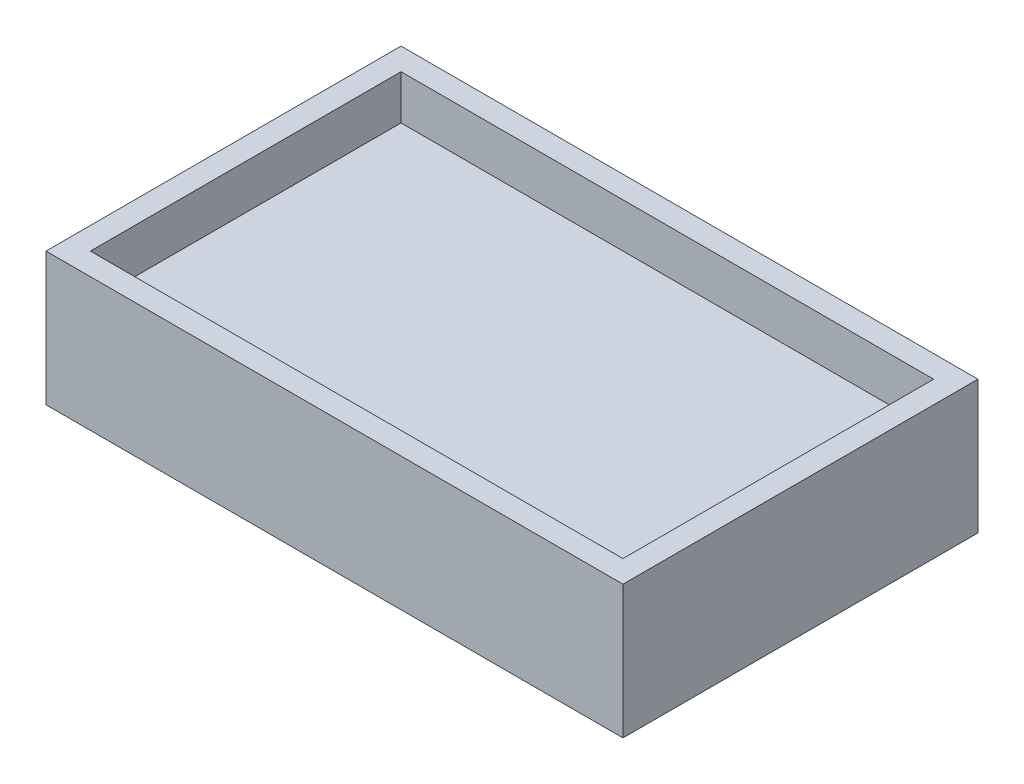
SolidWorks part; units mm, degrees
ref_plane "Front Plane" through (0, 0, 0) normal (0, 0, 1) x (1, 0, 0)
ref_plane "Top Plane" through (0, 0, 0) normal (0, 1, 0) x (1, 0, 0)
ref_plane "Right Plane" through (0, 0, 0) normal (1, 0, 0) x (0, 0, -1)
sketch "Sketch2" plane through (0, 0, 0) normal (0, 1, 0) x (1, 0, 0)
  line L1 (-65, 40) -> (65, 40)
  line L2 (-65, 40) -> (-65, -40)
  line L3 (-65, -40) -> (65, -40)
  line L4 (65, 40) -> (65, -40)
  line L5 (-65, 40) -> (65, -40) construction
  line L6 (-65, -40) -> (65, 40) construction
  point P0 (0, 0)
  dimension "D1" = 130
  dimension "D2" = 80
extrude "Boss-Extrude1" add sketch "Sketch2" along normal blind 25
sketch "Sketch5" plane through (0, 25, 0) normal (0, 1, 0) x (1, 0, 0)
  line L0 (65, -40) -> (65, 40) construction
  line L1 (-60, 35) -> (60, 35)
  line L2 (-60, 35) -> (-60, -35)
  line L3 (-60, -35) -> (60, -35)
  line L4 (60, 35) -> (60, -35)
  line L5 (-60, 35) -> (60, -35) construction
  line L6 (-60, -35) -> (60, 35) construction
  line L7 (-65, -40) -> (65, -40) construction
  point P0 (0, 0)
  dimension "D1" = 5
  dimension "D2" = 5
extrude "Cut-Extrude1" cut sketch "Sketch5" against normal blind 10
sketch "Sketch6" plane through (0, 0, 0) normal (0, -1, 0) x (-1, 0, 0)
  line L1 (-65, -40) -> (65, -40)
  line L2 (-65, -40) -> (-65, 40)
  line L3 (-65, 40) -> (65, 40)
  line L4 (65, -40) -> (65, 40)
  line L5 (-65, -40) -> (65, 40) construction
  line L6 (-65, 40) -> (65, -40) construction
  point P0 (0, 0)
extrude "Boss-Extrude2" add sketch "Sketch6" along normal blind 5
